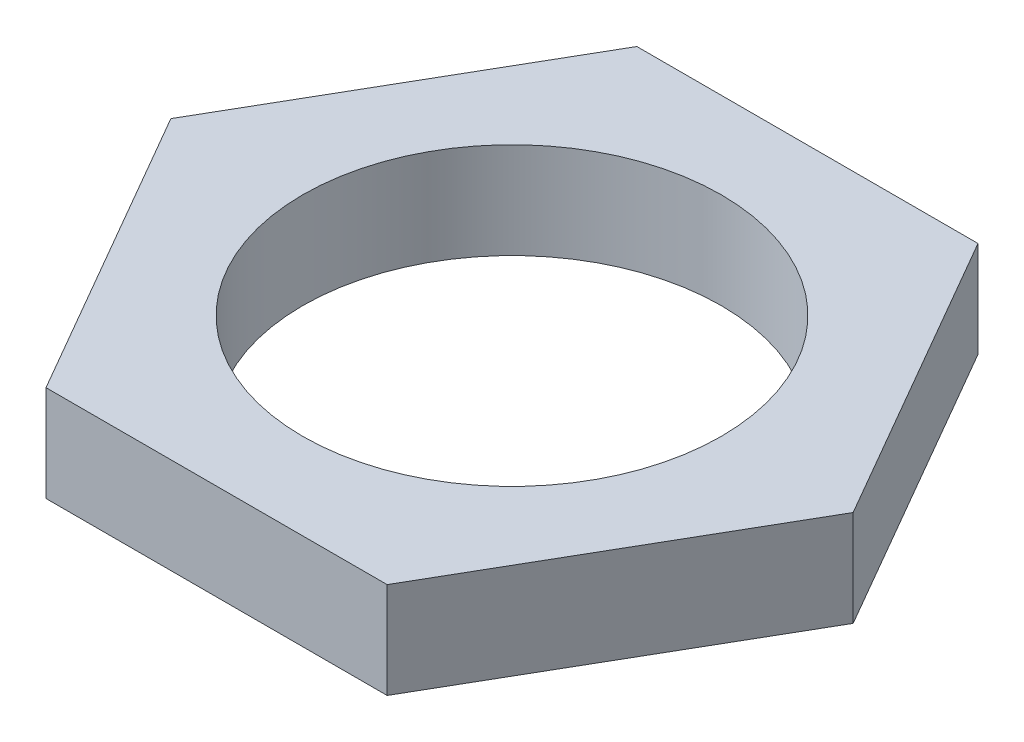
SolidWorks part; units mm, degrees
ref_plane "Front Plane" through (0, 0, 0) normal (0, 0, 1) x (1, 0, 0)
ref_plane "Top Plane" through (0, 0, 0) normal (0, 1, 0) x (1, 0, 0)
ref_plane "Right Plane" through (0, 0, 0) normal (1, 0, 0) x (0, 0, -1)
sketch "Sketch2" plane through (0, 0, 0) normal (0, 1, 0) x (1, 0, 0)
  line L0 (-187.5089, 0) -> (9187.9382, 0) construction
  line L1 (6.9282, 12) -> (-6.9282, 12)
  line L2 (-6.9282, 12) -> (-13.8564, 0)
  line L3 (-13.8564, 0) -> (-6.9282, -12)
  line L4 (-6.9282, -12) -> (6.9282, -12)
  line L5 (6.9282, -12) -> (13.8564, 0)
  line L6 (13.8564, 0) -> (6.9282, 12)
  circle A0 centre (0, 0) radius 12 construction
  circle A1 centre (0, 0) radius 8.5
  dimension "D2" = 17
  dimension "D1" = 24
extrude "Boss-Extrude1" add sketch "Sketch2" along normal blind 3.9
